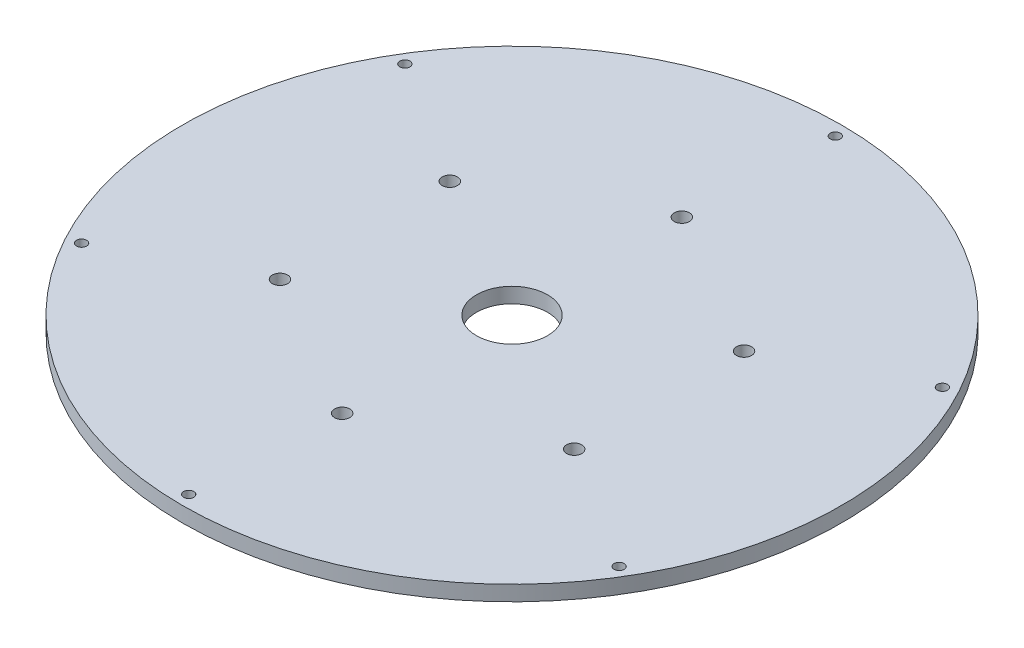
SolidWorks part; units mm, degrees
ref_plane "Plan de face" through (0, 0, 0) normal (0, 0, 1) x (1, 0, 0)
ref_plane "Plan de dessus" through (0, 0, 0) normal (0, 1, 0) x (1, 0, 0)
ref_plane "Plan de droite" through (0, 0, 0) normal (1, 0, 0) x (0, 0, -1)
sketch "Esquisse1" plane through (0, 0, 0) normal (0, 1, 0) x (1, 0, 0)
  circle A0 centre (0, 0) radius 65
extrude "Boss.-Extru.1" add sketch "Esquisse1" along normal blind 3
sketch "Esquisse2" plane through (0, 3, 0) normal (0, 1, 0) x (1, 0, 0)
  circle A2 centre (-53.4759, 32.3509) radius 1
  circle A3 centre (-54.7547, -30.136) radius 1
  circle A4 centre (-1.2788, -62.4869) radius 1
  circle A5 centre (53.4759, -32.3509) radius 1
  circle A6 centre (54.7547, 30.136) radius 1
  circle A7 centre (1.2788, 62.4869) radius 1
extrude "Enlèv. mat.-Extru.1" cut sketch "Esquisse2" against normal blind 3
sketch "Esquisse3" plane through (0, 3, 0) normal (0, 1, 0) x (1, 0, 0)
  circle A0 centre (0, 0) radius 7
extrude "Enlèv. mat.-Extru.2" cut sketch "Esquisse3" against normal blind 3
sketch "Esquisse4" plane through (0, 3, 0) normal (0, 1, 0) x (1, 0, 0)
  circle A1 centre (0, 33.5) radius 1.5
  circle A2 centre (29.0119, 16.75) radius 1.5
  circle A3 centre (29.0119, -16.75) radius 1.5
  circle A4 centre (0, -33.5) radius 1.5
  circle A5 centre (-29.0119, -16.75) radius 1.5
  circle A6 centre (-29.0119, 16.75) radius 1.5
extrude "Enlèv. mat.-Extru.4" cut sketch "Esquisse4" against normal blind 4
